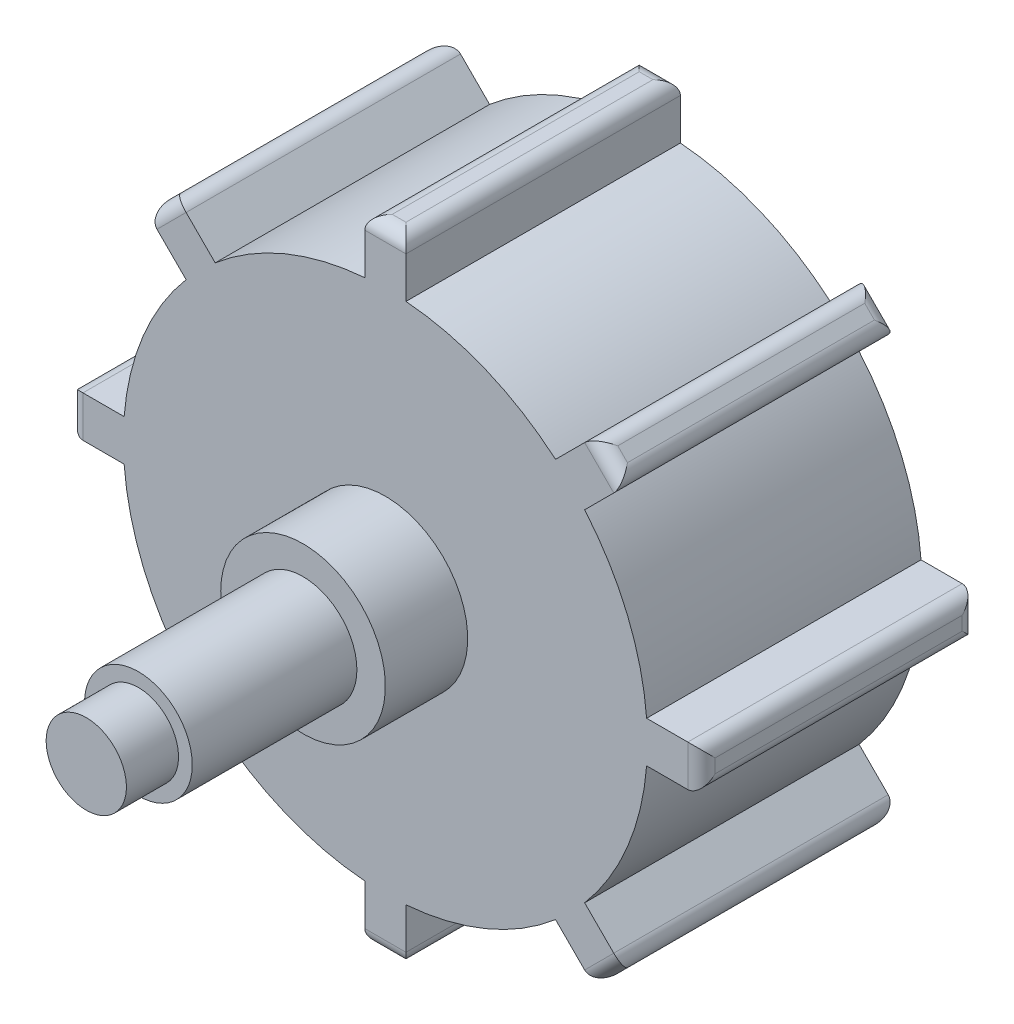
SolidWorks part; units mm, degrees
ref_plane "Ebene vorne" through (0, 0, 0) normal (0, 0, 1) x (1, 0, 0)
ref_plane "Ebene oben" through (0, 0, 0) normal (0, 1, 0) x (1, 0, 0)
ref_plane "Ebene rechts" through (0, 0, 0) normal (1, 0, 0) x (0, 0, -1)
sketch "Skizze1" plane through (0, 0, 0) normal (0, 0, 1) x (1, 0, 0)
  circle A0 centre (0, 0) radius 3.925
  dimension "D1" = 7.85
extrude "Aufsatz-Linear austragen1" add sketch "Skizze1" along normal blind 12
sketch "Skizze2" plane through (0, 0, 0) normal (0, 0, -1) x (-1, 0, 0)
  circle A0 centre (0, 0) radius 6
  dimension "D1" = 12
extrude "Aufsatz-Linear austragen2" add sketch "Skizze2" along normal blind 6
sketch "Skizze3" plane through (0, 0, -6) normal (0, 0, -1) x (-1, 0, 0)
  circle A0 centre (0, 0) radius 19.0986
  dimension "D1" = 38.1972
extrude "Aufsatz-Linear austragen3" add sketch "Skizze3" along normal blind 20
sketch "Skizze4" plane through (0, 0, -26) normal (0, 0, -1) x (-1, 0, 0)
  circle A0 centre (0, 0) radius 6.075
  dimension "D1" = 12.15
extrude "Schnitt-Linear austragen1" cut sketch "Skizze4" against normal blind 10
fillet "Verrundung1" radius 1 1 edges at (-6.075, 0, -26)
sketch "Skizze5" plane through (0, 0, -26) normal (0, 0, -1) x (-1, 0, 0)
  line L0 (0, 0) -> (0, 23.0396) construction
  line L1 (-1.5, 19.0396) -> (-1.5, 23.0396)
  line L2 (-1.5, 23.0396) -> (0, 23.0396)
  line L3 (0, 23.0396) -> (1.5, 23.0396)
  line L4 (1.5, 23.0396) -> (1.5, 19.0396)
  line L5 (-1.5, 19.0396) -> (1.5, 19.0396)
  circle A0 centre (0, 0) radius 19.0986 construction
  circle A2 centre (0, 0) radius 19.0986
  arc A3 (-1.5, 19.0396) -> (1.5, 19.0396) centre (0, 0) ccw
  circle M5 centre (0, 0) radius 19.0986
  dimension "D1" = 1.5
  dimension "D2" = 1.5
  dimension "D3" = 4
  dimension "D4" = 0
extrude "Aufsatz-Linear austragen4" add sketch "Skizze5" against normal up to surface (20 mm away) contours L0 L4 L3 M5 | L0 L2 L1 M5 up to face at (-6, 0, -6)
fillet "Verrundung2" radius 1 4 edges at (1.5, 23.0396, -16) (-1.5, 23.0396, -16) (0, 23.0396, -26) (0, 23.0396, -6)
pattern_circular "Kreismuster1" count 8 over 360 about axis through (0, 0, 0) along (0, 0, 1) of "Verrundung2", "Aufsatz-Linear austragen4"
sketch "Skizze6" plane through (0, 0, 12) normal (0, 0, 1) x (1, 0, 0)
  circle A0 centre (0, 0) radius 2.925
  dimension "D1" = 5.85
extrude "Aufsatz-Linear austragen5" add sketch "Skizze6" along normal blind 3.8
